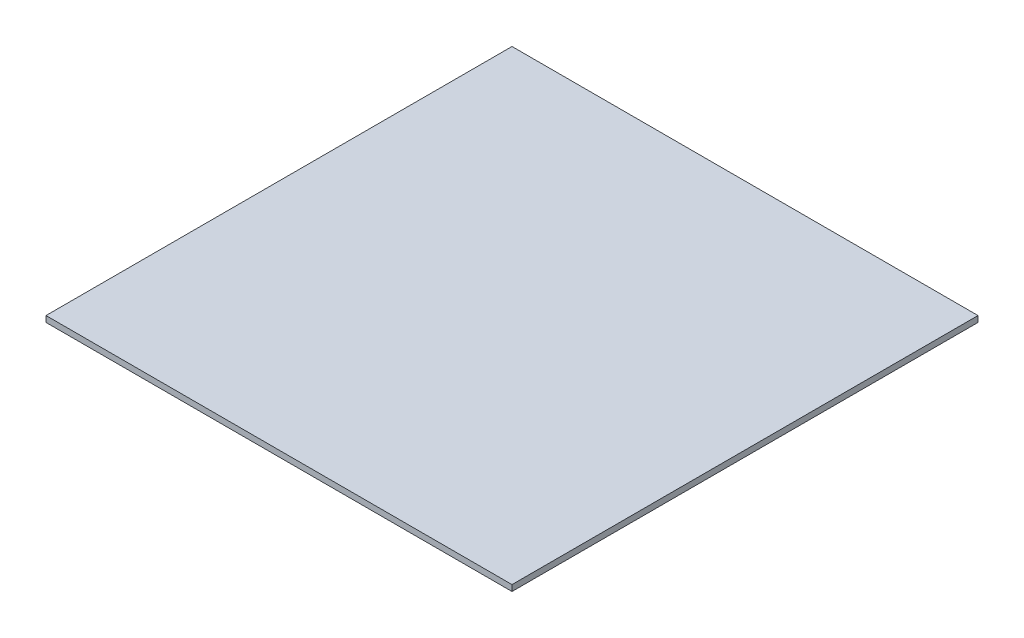
SolidWorks part; units mm, degrees
ref_plane "Спереди" through (0, 0, 0) normal (0, 0, 1) x (1, 0, 0)
ref_plane "Сверху" through (0, 0, 0) normal (0, 1, 0) x (1, 0, 0)
ref_plane "Справа" through (0, 0, 0) normal (1, 0, 0) x (0, 0, -1)
sketch "Эскиз1" plane through (0, 0, 0) normal (0, 1, 0) x (1, 0, 0)
  line L1 (0, 0) -> (310, 0)
  line L2 (0, 0) -> (0, 310)
  line L3 (0, 310) -> (310, 310)
  line L4 (310, 0) -> (310, 310)
  dimension "D1" = 310
  dimension "D2" = 310
extrude "Бобышка-Вытянуть1" add sketch "Эскиз1" along normal blind 4
sketch "Эскиз2" plane through (0, 0, 0) normal (0, -1, 0) x (1, 0, 0)
  line L0 (37.5, -37.5) -> (37.5, -272.5) construction
  line L1 (37.5, -272.5) -> (272.5, -272.5) construction
  line L2 (272.5, -272.5) -> (272.5, -37.5) construction
  line L3 (272.5, -37.5) -> (37.5, -37.5) construction
  line L4 (0, -310) -> (0, 0) construction
  line L5 (0, 0) -> (310, 0) construction
  circle A0 centre (272.5, -37.5) radius 2
  circle A1 centre (272.5, -272.5) radius 2
  circle A2 centre (37.5, -37.5) radius 2
  circle A3 centre (37.5, -272.5) radius 2
  point P2 (37.5, -155)
  point P13 (0, -155)
  point P14 (155, 0)
  point P17 (155, -37.5)
  dimension "D3" = 4
  dimension "D1" = 235
  dimension "D2" = 235
extrude "Бобышка-Вытянуть2" add sketch "Эскиз2" along normal blind 25
